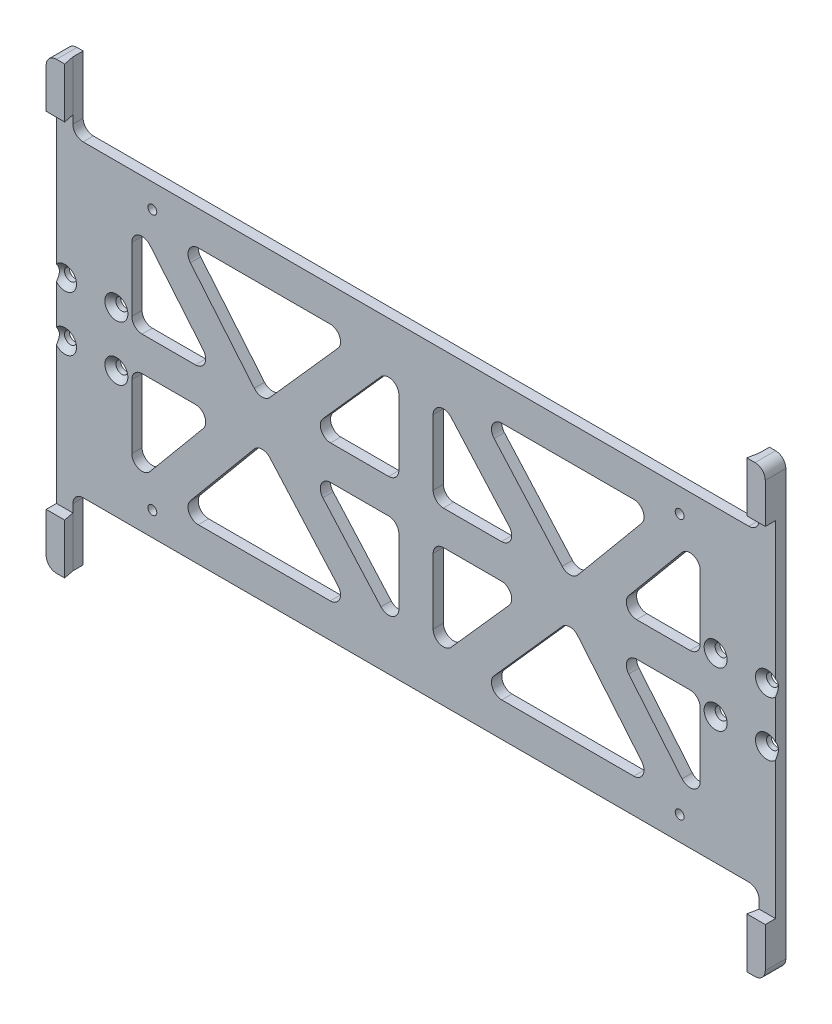
SolidWorks part; units mm, degrees
ref_plane "前视基准面" through (0, 0, 0) normal (0, 0, 1) x (1, 0, 0)
ref_plane "上视基准面" through (0, 0, 0) normal (0, 1, 0) x (1, 0, 0)
ref_plane "右视基准面" through (0, 0, 0) normal (1, 0, 0) x (0, 0, -1)
sketch "草图1" plane through (0, 0, 0) normal (0, 0, 1) x (1, 0, 0)
  line L0 (105, 90) -> (105, -49910) construction
  line L1 (7.8, 0) -> (202.2, 0)
  line L2 (0, 0) -> (0, 90)
  line L3 (7.8, 90) -> (202.2, 90)
  line L4 (210, 0) -> (210, 90)
  line L5 (0, 45) -> (210, 45) construction
  line L6 (10, 48.9878) -> (10, -49951.0122) construction
  line L7 (205.2, 93) -> (205.2, 110)
  line L8 (3, -20) -> (4.8, -20)
  line L9 (0, 90) -> (0, 107)
  line L10 (3, 110) -> (4.8, 110)
  line L11 (4.8, 93) -> (4.8, 110)
  line L12 (207, 110) -> (205.2, 110)
  line L13 (210, 90) -> (210, 107)
  line L14 (22, 71.7103) -> (22, 53)
  line L15 (207, -20) -> (205.2, -20)
  line L16 (210, 0) -> (210, -17)
  line L17 (205.2, -3) -> (205.2, -20)
  line L18 (4.8, -3) -> (4.8, -20)
  line L19 (0, 0) -> (0, -17)
  line L20 (25, 50) -> (40.5831, 50)
  line L21 (42.8883, 54.9199) -> (27.3052, 73.6302)
  line L22 (39.1117, 75.0801) -> (57.7672, 52.6808)
  line L23 (62.316, 52.6093) -> (82.1982, 75.0085)
  line L24 (79.9546, 80) -> (41.4169, 80)
  line L25 (100, 72.101) -> (100, 53)
  line L26 (97, 50) -> (80.0454, 50)
  line L27 (77.8018, 54.9915) -> (94.7564, 74.0925)
  line L28 (113, 50) -> (129.9546, 50)
  line L29 (110, 72.101) -> (110, 53)
  line L30 (132.1982, 54.9915) -> (115.2436, 74.0925)
  line L31 (147.684, 52.6093) -> (127.8018, 75.0085)
  line L32 (130.0454, 80) -> (168.5831, 80)
  line L33 (170.8883, 75.0801) -> (152.2328, 52.6808)
  line L34 (167.1117, 54.9199) -> (182.6948, 73.6302)
  line L35 (185, 50) -> (169.4169, 50)
  line L36 (188, 71.7103) -> (188, 53)
  line L37 (185, 40) -> (169.4169, 40)
  line L38 (188, 18.2897) -> (188, 37)
  line L39 (167.1117, 35.0801) -> (182.6948, 16.3698)
  line L40 (170.8883, 14.9199) -> (152.2328, 37.3192)
  line L41 (130.0454, 10) -> (168.5831, 10)
  line L42 (147.684, 37.3907) -> (127.8018, 14.9915)
  line L43 (113, 40) -> (129.9546, 40)
  line L44 (110, 17.899) -> (110, 37)
  line L45 (132.1982, 35.0085) -> (115.2436, 15.9075)
  line L46 (97, 40) -> (80.0454, 40)
  line L47 (100, 17.899) -> (100, 37)
  line L48 (77.8018, 35.0085) -> (94.7564, 15.9075)
  line L49 (62.316, 37.3907) -> (82.1982, 14.9915)
  line L50 (79.9546, 10) -> (41.4169, 10)
  line L51 (39.1117, 14.9199) -> (57.7672, 37.3192)
  line L52 (42.8883, 35.0801) -> (27.3052, 16.3698)
  line L53 (25, 40) -> (40.5831, 40)
  line L54 (22, 18.2897) -> (22, 37)
  circle A0 centre (2.5, 53) radius 1.75
  circle A1 centre (17.5, 53) radius 1.75
  circle A2 centre (17.5, 37) radius 1.75
  circle A3 centre (2.5, 37) radius 1.75
  circle A4 centre (207.5, 37) radius 1.75
  circle A5 centre (192.5, 37) radius 1.75
  circle A6 centre (192.5, 53) radius 1.75
  circle A7 centre (207.5, 53) radius 1.75
  arc A8 (205.2, 93) -> (202.2, 90) centre (202.2, 93) cw
  arc A9 (7.8, 90) -> (4.8, 93) centre (7.8, 93) cw
  arc A10 (4.8, -3) -> (7.8, 0) centre (7.8, -3) cw
  arc A11 (205.2, -3) -> (202.2, 0) centre (202.2, -3) ccw
  arc A12 (185, 50) -> (188, 53) centre (185, 53) ccw
  arc A13 (167.1117, 54.9199) -> (169.4169, 50) centre (169.4169, 53) ccw
  arc A14 (182.6948, 73.6302) -> (188, 71.7103) centre (185, 71.7103) cw
  arc A15 (168.5831, 80) -> (170.8883, 75.0801) centre (168.5831, 77) cw
  arc A16 (127.8018, 75.0085) -> (130.0454, 80) centre (130.0454, 77) cw
  arc A17 (113, 50) -> (110, 53) centre (113, 53) cw
  arc A18 (110, 72.101) -> (115.2436, 74.0925) centre (113, 72.101) cw
  arc A19 (129.9546, 50) -> (132.1982, 54.9915) centre (129.9546, 53) ccw
  arc A20 (169.4169, 40) -> (167.1117, 35.0801) centre (169.4169, 37) ccw
  arc A21 (185, 40) -> (188, 37) centre (185, 37) cw
  arc A22 (188, 18.2897) -> (182.6948, 16.3698) centre (185, 18.2897) cw
  arc A23 (170.8883, 14.9199) -> (168.5831, 10) centre (168.5831, 13) cw
  arc A24 (130.0454, 10) -> (127.8018, 14.9915) centre (130.0454, 13) cw
  arc A25 (152.2328, 37.3192) -> (147.684, 37.3907) centre (149.9276, 35.3992) ccw
  arc A26 (129.9546, 40) -> (132.1982, 35.0085) centre (129.9546, 37) cw
  arc A27 (113, 40) -> (110, 37) centre (113, 37) ccw
  arc A28 (110, 17.899) -> (115.2436, 15.9075) centre (113, 17.899) ccw
  arc A29 (82.1982, 14.9915) -> (79.9546, 10) centre (79.9546, 13) cw
  arc A30 (100, 17.899) -> (94.7564, 15.9075) centre (97, 17.899) cw
  arc A31 (80.0454, 40) -> (77.8018, 35.0085) centre (80.0454, 37) ccw
  arc A32 (97, 40) -> (100, 37) centre (97, 37) cw
  arc A33 (100, 53) -> (97, 50) centre (97, 53) cw
  arc A34 (100, 72.101) -> (94.7564, 74.0925) centre (97, 72.101) ccw
  arc A35 (80.0454, 50) -> (77.8018, 54.9915) centre (80.0454, 53) cw
  arc A36 (57.7672, 52.6808) -> (62.316, 52.6093) centre (60.0724, 54.6008) ccw
  arc A37 (62.316, 37.3907) -> (57.7672, 37.3192) centre (60.0724, 35.3992) ccw
  arc A38 (41.4169, 10) -> (39.1117, 14.9199) centre (41.4169, 13) cw
  arc A39 (27.3052, 16.3698) -> (22, 18.2897) centre (25, 18.2897) cw
  arc A40 (25, 40) -> (22, 37) centre (25, 37) ccw
  arc A41 (42.8883, 35.0801) -> (40.5831, 40) centre (40.5831, 37) ccw
  arc A42 (40.5831, 50) -> (42.8883, 54.9199) centre (40.5831, 53) ccw
  arc A43 (22, 53) -> (25, 50) centre (25, 53) ccw
  arc A44 (22, 71.7103) -> (27.3052, 73.6302) centre (25, 71.7103) cw
  arc A45 (39.1117, 75.0801) -> (41.4169, 80) centre (41.4169, 77) cw
  arc A46 (82.1982, 75.0085) -> (79.9546, 80) centre (79.9546, 77) ccw
  arc A47 (147.684, 52.6093) -> (152.2328, 52.6808) centre (149.9276, 54.6008) ccw
  arc A48 (207, 110) -> (210, 107) centre (207, 107) cw
  arc A49 (207, -20) -> (210, -17) centre (207, -17) ccw
  arc A50 (0, -17) -> (3, -20) centre (3, -17) ccw
  arc A51 (0, 107) -> (3, 110) centre (3, 107) cw
  circle A52 centre (28, 83) radius 1.3
  circle A53 centre (182, 83) radius 1.3
  circle A54 centre (182, 7) radius 1.3
  circle A55 centre (28, 7) radius 1.3
  point P7 (105, 90)
  point P8 (105, 0)
  point P81 (205.2, 90)
  point P84 (4.8, 90)
  point P87 (4.8, 0)
  point P90 (205.2, 0)
  point P93 (188, 50)
  point P96 (163.0141, 50)
  point P99 (188, 80)
  point P102 (174.9859, 80)
  point P105 (123.3712, 80)
  point P108 (110, 50)
  point P111 (110, 80)
  point P114 (136.6288, 50)
  point P117 (163.0141, 40)
  point P120 (188, 40)
  point P123 (188, 10)
  point P126 (174.9859, 10)
  point P129 (123.3712, 10)
  point P132 (150, 40)
  point P135 (136.6288, 40)
  point P138 (110, 40)
  point P141 (110, 10)
  point P144 (86.6288, 10)
  point P147 (100, 10)
  point P150 (73.3712, 40)
  point P153 (100, 40)
  point P156 (100, 50)
  point P159 (100, 80)
  point P162 (73.3712, 50)
  point P165 (60, 50)
  point P168 (60, 40)
  point P171 (35.0141, 10)
  point P174 (22, 10)
  point P177 (22, 40)
  point P180 (46.9859, 40)
  point P183 (46.9859, 50)
  point P186 (22, 50)
  point P189 (22, 80)
  point P192 (35.0141, 80)
  point P195 (86.6288, 80)
  point P196 (150, 50)
  point P199 (210, 110)
  point P202 (210, -20)
  point P205 (0, -20)
  point P208 (0, 110)
  point P213 (27.3978, 45)
  dimension "D3" = 3.5
  dimension "D17" = 3
  dimension "D18" = 3
  dimension "D19" = 3
  dimension "D22" = 2.6
  dimension "D1" = 90
  dimension "D2" = 175
  dimension "D4" = 10
  dimension "D5" = 15
  dimension "D6" = 16
  dimension "D7" = 210
  dimension "D8" = 4.8
  dimension "D9" = 20
  dimension "D10" = 10
  dimension "D11" = 5
  dimension "D12" = 5
  dimension "D13" = 10
  dimension "D14" = 10
  dimension "D15" = 22
  dimension "D16" = 60
  dimension "D20" = 77
  dimension "D21" = 38
extrude "凸台-拉伸1" add sketch "草图1" along normal blind 3
sketch "草图2" plane through (0, 0, 3) normal (0, 0, 1) x (1, 0, 0)
  line L0 (105, 90) -> (105, 0) construction
  line L1 (202.2, 90) -> (7.8, 90) construction
  line L2 (7.8, 0) -> (202.2, 0) construction
  line L3 (0, 45) -> (210, 45) construction
  line L4 (0, 107) -> (0, -17) construction
  line L5 (210, -17) -> (210, 107) construction
  line L6 (3, 110) -> (5.4, 110)
  line L8 (5.4, 95.3333) -> (0, 95.3333)
  line L9 (0, 107) -> (0, 95.3333)
  line L10 (204.6, 95.3333) -> (204.6, 110)
  line L11 (210, 107) -> (210, 95.3333)
  line L12 (5.4, 95.3333) -> (5.4, 110)
  line L13 (204.6, 95.3333) -> (210, 95.3333)
  line L14 (207, 110) -> (204.6, 110)
  line L15 (207, -20) -> (204.6, -20)
  line L16 (204.6, -5.3333) -> (210, -5.3333)
  line L17 (5.4, -5.3333) -> (5.4, -20)
  line L18 (210, -17) -> (210, -5.3333)
  line L19 (204.6, -5.3333) -> (204.6, -20)
  line L20 (0, -17) -> (0, -5.3333)
  line L21 (5.4, -5.3333) -> (0, -5.3333)
  line L22 (3, -20) -> (5.4, -20)
  arc A0 (3, 110) -> (0, 107) centre (3, 107) ccw
  arc A1 (207, 110) -> (210, 107) centre (207, 107) cw
  arc A2 (207, -20) -> (210, -17) centre (207, -17) ccw
  arc A3 (3, -20) -> (0, -17) centre (3, -17) cw
  dimension "D1" = 3
  dimension "D2" = 5.4
extrude "凸台-拉伸2" add sketch "草图2" along normal blind 3
sketch "草图3" plane through (0, 95.3333, 0) normal (0, -1, 0) x (1, 0, 0)
  line L0 (4.8, 3) -> (5.4, 6)
  line L1 (5.4, 6) -> (5.4, 3)
  line L2 (7.8, 3) -> (4.8, 3) construction
  line L3 (5.4, 6) -> (5.4, 3) construction
  line L4 (5.4, 3) -> (4.8, 3)
  line L5 (204.6, 3) -> (204.6, 6)
  line L6 (204.6, 6) -> (205.2, 3)
  line L7 (205.2, 3) -> (204.6, 3)
extrude "切除-拉伸1" cut sketch "草图3" against normal through all and the other way through all
hole_wizard "M3 六角凹锥坑螺钉的锥形沉头孔5" positions "3D草图10" profile "草图11" countersink size "M3" standard "ISO" end condition through all
sketch3d "3D草图10"
  line L0 (2.5, 53, 3) -> (2.5, 53, 0) construction
  line L1 (2.5, 37, 3) -> (2.5, 37, 0) construction
  line L2 (17.5, 37, 3) -> (17.5, 37, 0) construction
  line L3 (17.5, 53, 3) -> (17.5, 53, 0) construction
  line L4 (192.5, 53, 3) -> (192.5, 53, 0) construction
  line L5 (207.5, 37, 3) -> (207.5, 37, 0) construction
  line L6 (207.5, 53, 3) -> (207.5, 53, 0) construction
  line L7 (192.5, 37, 3) -> (192.5, 37, 0) construction
  point P0 (2.5, 53, 3)
  point P4 (2.5, 37, 3)
  point P8 (17.5, 37, 3)
  point P12 (17.5, 53, 3)
  point P16 (192.5, 53, 3)
  point P20 (207.5, 37, 3)
  point P24 (207.5, 53, 3)
  point P28 (192.5, 37, 3)
sketch "草图11" plane through (2.5, 53, 3) normal (1, 0, 0) x (0, -1, 0)
  line L0 (0, 0) -> (0, 3)
  line L1 (0, 3) -> (1.7, 3)
  line L2 (1.7, 3) -> (1.7, 1.66)
  line L3 (1.7, 1.66) -> (3.36, 0)
  line L5 (3.36, 0) -> (0, 0)
  line L6 (-1.7, 1.66) -> (-3.36, 0) construction
  line L11 (0, -6.35) -> (0, 107.95) construction
  dimension "通孔孔直径" = 3.4
  dimension "通孔孔深度" = 3
  dimension "近端锥形沉头孔直径" = 6.72
  dimension "近端锥形沉头孔角度" = 90
